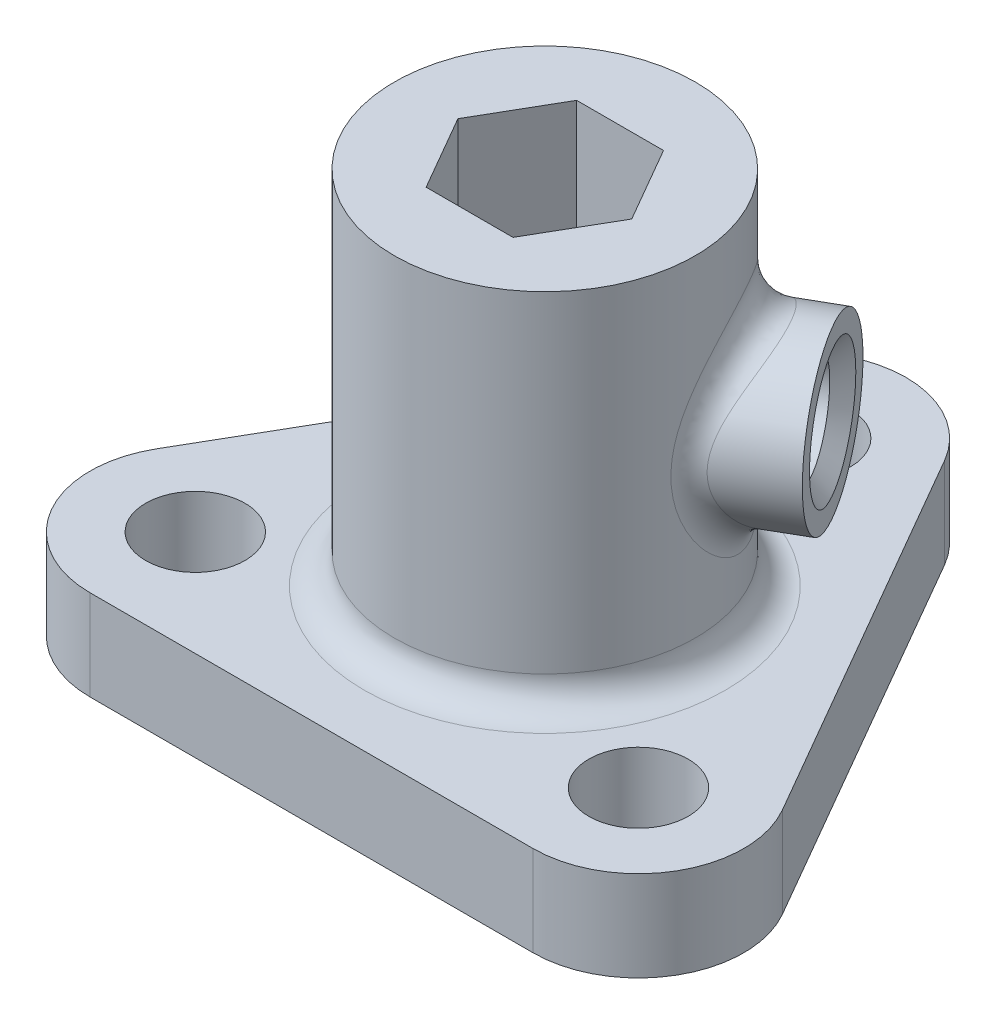
SolidWorks part; units mm, degrees
ref_plane "Front Plane" through (0, 0, 0) normal (0, 0, 1) x (1, 0, 0)
ref_plane "Top Plane" through (0, 0, 0) normal (0, 1, 0) x (1, 0, 0)
ref_plane "Right Plane" through (0, 0, 0) normal (1, 0, 0) x (0, 0, -1)
sketch "Sketch1" plane through (0, 0, 0) normal (1, 0, 0) x (0, 0, -1)
  line L1 (0, 0) -> (12, 0)
  line L2 (0, 0) -> (0, 5.3535)
  line L3 (5, 3) -> (12, 3)
  line L4 (12, 0) -> (12, 3)
  line L6 (0, 5.3535) -> (0, 15)
  line L7 (0, 15) -> (5, 15)
  line L8 (5, 3) -> (5, 15)
  dimension "D1" = 15
  dimension "6" = 5
  dimension "D3" = 3
  dimension "D4" = 7
revolve "Revolve1" add sketch "Sketch1" angle 360 about L6
sketch "Sketch4" plane through (0, 3, 0) normal (0, 1, 0) x (1, 0, 0)
  circle A0 centre (0, 8.5) radius 1.65
  circle A1 centre (7.3612, -4.25) radius 1.65
  circle A2 centre (-7.3612, -4.25) radius 1.65
  circle A6 centre (0, 0) radius 8.5 construction
  point P4 (0, 8.5)
  point P15 (0, 0)
  point P17 (0, 0)
  point P18 (13.8375, 8.8486)
  point P19 (0, 0)
  dimension "D2" = 17
  dimension "D3" = 3.3
  dimension "D1" = 3
extrude "Cut-Extrude4" cut sketch "Sketch4" against normal through all
sketch "Sketch5" plane through (0, 3, 0) normal (0, 1, 0) x (1, 0, 0)
  line L0 (-3.0311, 10.25) -> (-10.3923, -2.5)
  line L1 (-7.3612, -7.75) -> (7.3612, -7.75)
  line L2 (3.0311, 10.25) -> (10.3923, -2.5)
  arc A0 (3.0311, 10.25) -> (-3.0311, 10.25) centre (0, 8.5) ccw
  arc A1 (7.3612, -7.75) -> (10.3923, -2.5) centre (7.3612, -4.25) ccw
  arc A2 (-10.3923, -2.5) -> (-7.3612, -7.75) centre (-7.3612, -4.25) ccw
  circle A3 centre (0, 0) radius 12 construction
  point P15 (0, 0)
extrude "Cut-Extrude5" cut sketch "Sketch5" against normal through all flip side to cut
sketch "Sketch2" plane through (0, 15, 0) normal (0, 1, 0) x (1, 0, 0)
  line L0 (10.3923, -2.5) -> (3.0311, 10.25) construction
  line L1 (2.8868, 0) -> (1.4434, 2.5)
  line L2 (1.4434, 2.5) -> (-1.4434, 2.5)
  line L3 (-1.4434, 2.5) -> (-2.8868, 0)
  line L4 (-2.8868, 0) -> (-1.4434, -2.5)
  line L5 (-1.4434, -2.5) -> (1.4434, -2.5)
  line L6 (1.4434, -2.5) -> (2.8868, 0)
  circle A0 centre (0, 0) radius 2.5 construction
  point P1 (0, 2.8868)
  point P10 (0, 0)
  dimension "D1" = 5
extrude "Cut-Extrude2" cut sketch "Sketch2" against normal offset from surface (16 mm away) 4 up to face at (0, 3, -6.85) offset beyond the face yes
ref_plane "Plane1" through (6.0622, 0, -3.5) normal (-0.866, 0, 0.5) x (0.5, 0, 0.866)
sketch "Sketch3" plane through (6.0622, 0, -3.5) normal (0.866, 0, -0.5) x (-0.5, 0, -0.866)
  line L0 (0, 15) -> (0, 3) construction
  line L1 (1.4434, 15) -> (-1.4434, 15) construction
  line L3 (5, 3) -> (-5, 3) construction
  circle A0 centre (0, 9) radius 2.75
  point P7 (0, 3.056)
  point P8 (0, 3.5581)
  point P9 (0, 0)
  point P10 (0, 9)
  point P11 (0, 3)
  point P12 (0, 3)
  dimension "D1" = 5.5
extrude "Boss-Extrude1" add sketch "Sketch3" against normal up to next
sketch "Sketch6" plane through (6.0622, 0, -3.5) normal (0.866, 0, -0.5) x (-0.5, 0, -0.866)
  circle A0 centre (0, 9) radius 1.6
  dimension "D1" = 3.2
extrude "Cut-Extrude6" cut sketch "Sketch6" against normal up to next
fillet "Fillet1" radius 1 1 edges at (0, 3, -5)
chamfer "Chamfer1" distance 0.5 angle 45 1 edges at (5.2622, 9, -4.8856)
fillet "Fillet2" radius 1 1 edges at (4.9921, 8.766, 0.2817)
